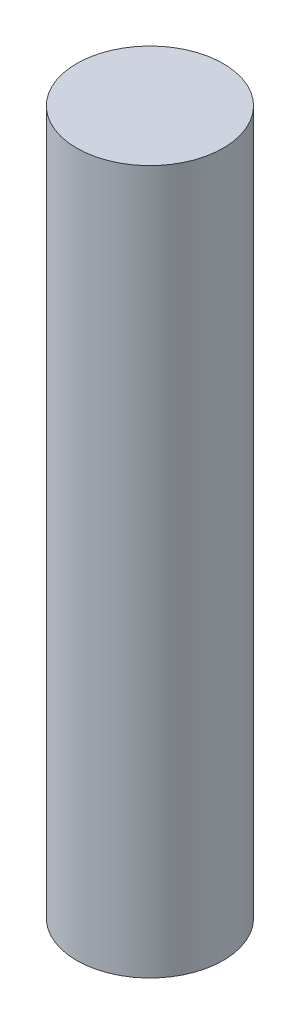
SolidWorks part; units mm, degrees
ref_plane "Front Plane" through (0, 0, 0) normal (0, 0, 1) x (1, 0, 0)
ref_plane "Top Plane" through (0, 0, 0) normal (0, 1, 0) x (1, 0, 0)
ref_plane "Right Plane" through (0, 0, 0) normal (1, 0, 0) x (0, 0, -1)
sketch "Sketch1" plane through (0, 0, 0) normal (0, 1, 0) x (1, 0, 0)
  circle A0 centre (0, 0) radius 2.5
  dimension "D1" = 5
extrude "Boss-Extrude1" add sketch "Sketch1" against normal blind 22 and the other way blind 2
